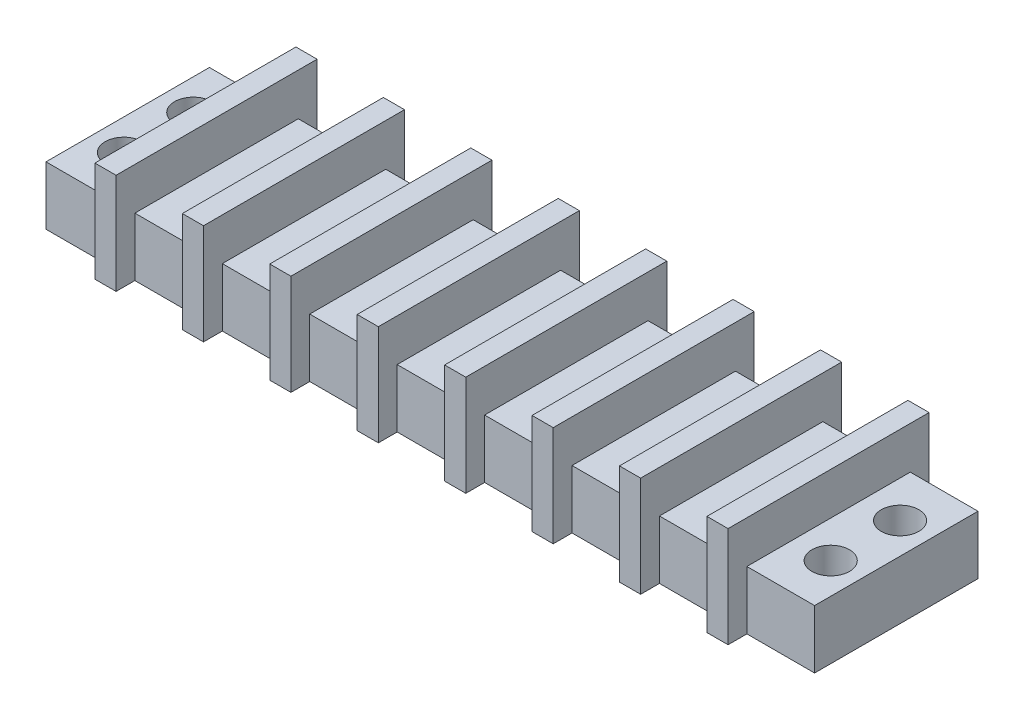
SolidWorks part; units mm, degrees
ref_plane "Front" through (0, 0, 0) normal (0, 0, 1) x (1, 0, 0)
ref_plane "Top" through (0, 0, 0) normal (0, 1, 0) x (1, 0, 0)
ref_plane "Right" through (0, 0, 0) normal (1, 0, 0) x (0, 0, -1)
sketch "Sketch1" plane through (0, 0, 0) normal (0, 1, 0) x (1, 0, 0)
  line L1 (0, 0) -> (83.0326, 0)
  line L2 (0, 0) -> (0, 17.653)
  line L3 (0, 17.653) -> (83.0326, 17.653)
  line L4 (83.0326, 0) -> (83.0326, 17.653)
  dimension "D1" = 83.0326
  dimension "D2" = 17.653
extrude "Boss-Extrude1" add sketch "Sketch1" along normal blind 6.3119
sketch "Sketch5" plane through (0, 0, 0) normal (0, -1, 0) x (1, 0, 0)
  line L0 (0, 0) -> (83.0326, 0) construction
  line L1 (7.3152, 2.032) -> (9.6012, 2.032)
  line L2 (7.3152, 2.032) -> (7.3152, -19.685)
  line L3 (7.3152, -19.685) -> (9.6012, -19.685)
  line L4 (9.6012, 2.032) -> (9.6012, -19.685)
  line L5 (0, -17.653) -> (0, 0) construction
  line L6 (83.0326, -17.653) -> (0, -17.653) construction
  dimension "D1" = 2.032
  dimension "D2" = 2.286
  dimension "D3" = 7.3152
  dimension "D4" = 2.032
extrude "Boss-Extrude5" add sketch "Sketch5" against normal blind 10.8712
sketch "Sketch8" plane through (0, 6.3119, 0) normal (0, 1, 0) x (1, 0, 0)
  line L0 (83.0326, 0) -> (75.7174, 0)
  line L1 (9.6012, 0) -> (83.0326, 0) construction
  line L2 (0, 0) -> (7.3152, 0) construction
pattern_linear "LPattern2" count 8 spacing 9.4452 along (1, 0, 0) of "Boss-Extrude5"
sketch "Sketch9" plane through (0, 6.3119, 0) normal (0, 1, 0) x (1, 0, 0)
  line L0 (0, 17.653) -> (0, 0) construction
  line L1 (0, 0) -> (7.3152, 0) construction
  circle A0 centre (3.3401, 5.08) radius 2.032
  dimension "D1" = 4.064
  dimension "D2" = 3.3401
  dimension "D3" = 5.08
extrude "Cut-Extrude1" cut sketch "Sketch9" against normal through all
ref_plane "Plane6" through (0, 0, -8.8265) normal (0, 0, 1) x (1, 0, 0)
mirror "Mirror1" about plane through (0, 0, -8.8265) normal (0, 0, 1) of "Cut-Extrude1"
ref_plane "Plane7" through (41.5163, 0, 0) normal (-1, 0, 0) x (0, 0, 1)
mirror "Mirror2" about plane through (41.5163, 0, 0) normal (-1, 0, 0) of "Mirror1", "Cut-Extrude1"
